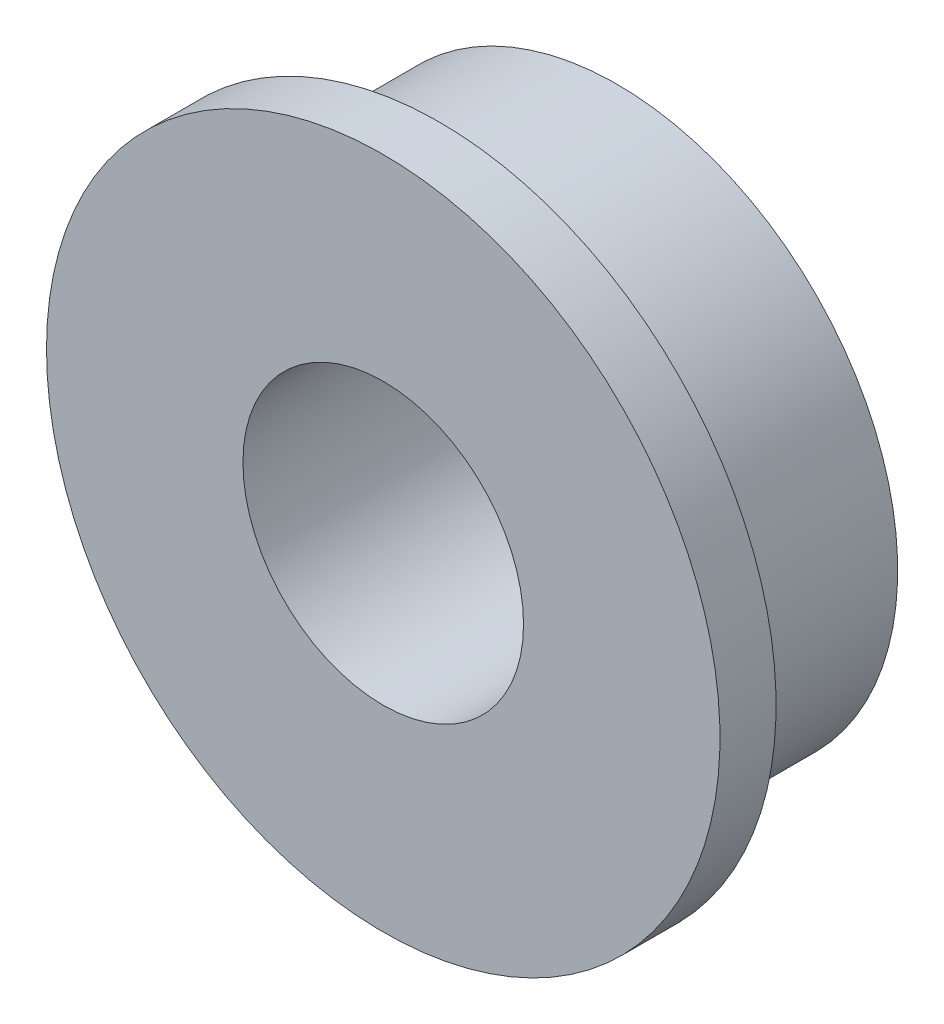
SolidWorks part; units mm, degrees
material "轴承钢"
ref_plane "前视基准面" through (0, 0, 0) normal (0, 0, 1) x (1, 0, 0)
ref_plane "上视基准面" through (0, 0, 0) normal (0, 1, 0) x (1, 0, 0)
ref_plane "右视基准面" through (0, 0, 0) normal (1, 0, 0) x (0, 0, -1)
sketch "草图1" plane through (0, 0, 0) normal (0, 1, 0) x (1, 0, 0)
  line L0 (0, 3) -> (0, -3.0541) construction
  line L1 (1.5, 0) -> (1.5, 2.5)
  line L2 (1.5, 2.5) -> (3, 2.5)
  line L3 (3, 2.5) -> (3, 0.6)
  line L4 (3, 0.6) -> (3.6, 0.6)
  line L5 (3.6, 0.6) -> (3.6, 0)
  line L6 (3.6, 0) -> (1.5, 0)
  point P8 (3.6, 0.3)
  dimension "D1" = 3
  dimension "D2" = 6
  dimension "D3" = 2.5
  dimension "D4" = 7.2
  dimension "D5" = 0.6
revolve "旋转1" add sketch "草图1" angle 360 about L0
